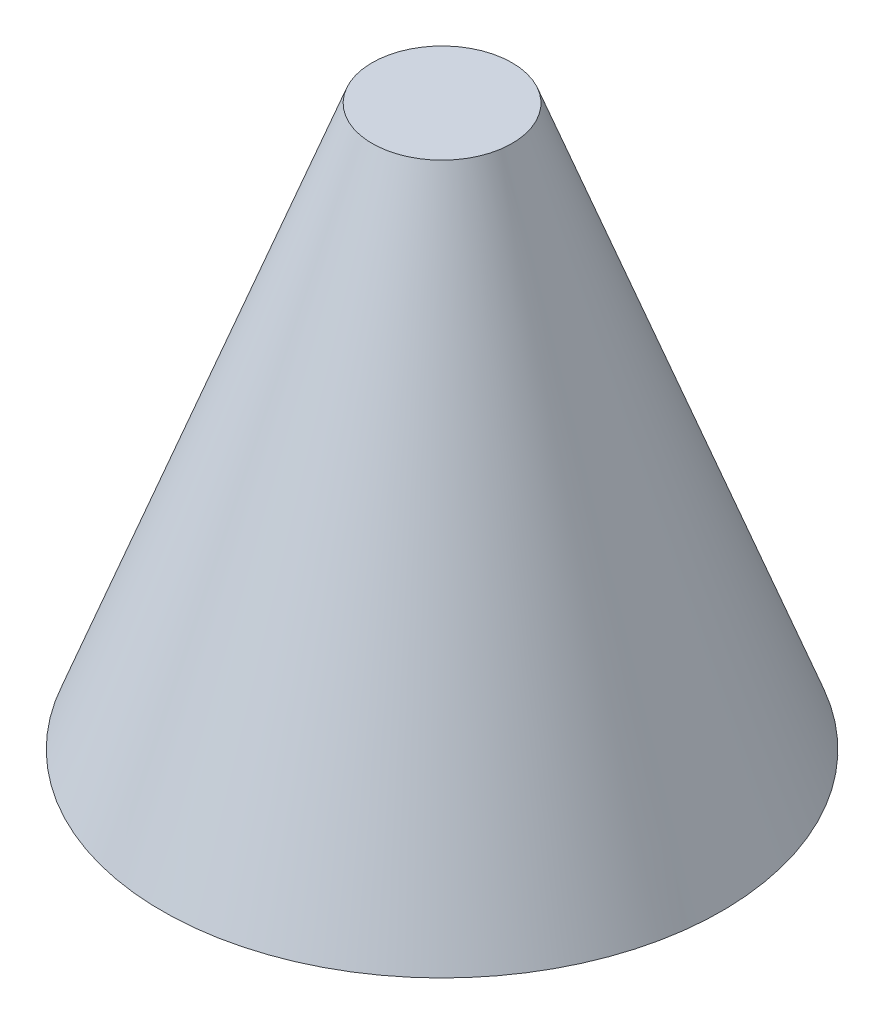
SolidWorks part; units mm, degrees
material "PS Średni/wysoki przepływ"
ref_plane "Płaszczyzna przednia" through (0, 0, 0) normal (0, 0, 1) x (1, 0, 0)
ref_plane "Płaszczyzna górna" through (0, 0, 0) normal (0, 1, 0) x (1, 0, 0)
ref_plane "Płaszczyzna prawa" through (0, 0, 0) normal (1, 0, 0) x (0, 0, -1)
sketch "Szkic1" plane through (0, 0, 0) normal (0, 0, 1) x (1, 0, 0)
  line L0 (0, 0) -> (0, 6) construction
  line L1 (0, 0) -> (-3, 0)
  line L2 (0, 6) -> (-0.75, 6)
  line L3 (-0.75, 6) -> (-3, 0)
  line L4 (0, 0) -> (0, 6)
  dimension "D1" = 6
  dimension "D2" = 3
  dimension "D3" = 0.75
revolve "Obrót1" add sketch "Szkic1" angle 360 about L0
sketch "Szkic2" plane through (0, 6, 0) normal (0, 1, 0) x (1, 0, 0)
  point P0 (0, 0)
